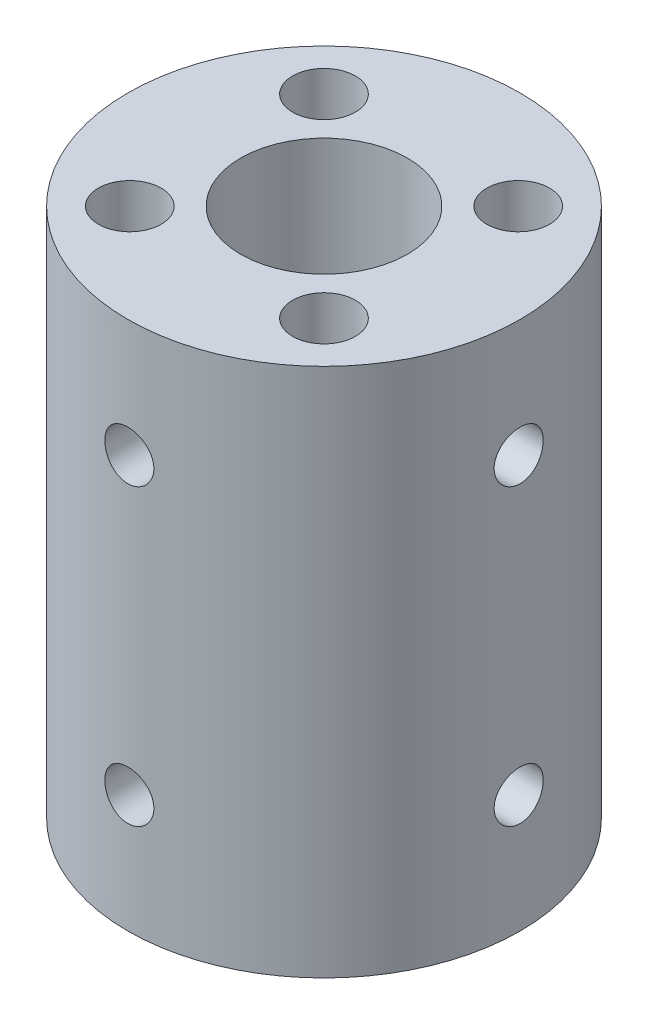
SolidWorks part; units mm, degrees
ref_plane "前视基准面" through (0, 0, 0) normal (0, 0, 1) x (1, 0, 0)
ref_plane "上视基准面" through (0, 0, 0) normal (0, 1, 0) x (1, 0, 0)
ref_plane "右视基准面" through (0, 0, 0) normal (1, 0, 0) x (0, 0, -1)
other "Configuration Table"
sketch "草图1" plane through (0, 0, 0) normal (0, 1, 0) x (1, 0, 0)
  line L1 (4.9497, 4.9497) -> (-4.9497, 4.9497) construction
  line L2 (4.9497, 4.9497) -> (4.9497, -4.9497) construction
  line L3 (4.9497, -4.9497) -> (-4.9497, -4.9497) construction
  line L4 (-4.9497, 4.9497) -> (-4.9497, -4.9497) construction
  line L5 (4.9497, 4.9497) -> (-4.9497, -4.9497) construction
  line L6 (4.9497, -4.9497) -> (-4.9497, 4.9497) construction
  circle A0 centre (0, 0) radius 10
  circle A1 centre (0, 0) radius 4.25
  circle A2 centre (-4.9497, 4.9497) radius 1.6
  circle A3 centre (-4.9497, -4.9497) radius 1.6
  circle A4 centre (4.9497, -4.9497) radius 1.6
  circle A5 centre (4.9497, 4.9497) radius 1.6
  dimension "D1" = 8.5
  dimension "D2" = 20
  dimension "D4" = 3.2
  dimension "D3" = 14
extrude "凸台-拉伸1" add sketch "草图1" along normal mid plane 27
sketch "草图2" plane through (0, 0, 0) normal (0, 0, 1) x (1, 0, 0)
  line L0 (0, -7.5) -> (0, 7.5) construction
  circle A0 centre (0, 7.5) radius 1.25
  circle A1 centre (0, -7.5) radius 1.25
  point P4 (0, 0)
  dimension "D1" = 2.5
  dimension "D2" = 15
extrude "切除-拉伸1" cut sketch "草图2" against normal through all
pattern_circular "阵列(圆周)1" count 4 over 360 about axis through (0, 13.5, 0) along (0, 1, 0) of "切除-拉伸1"
